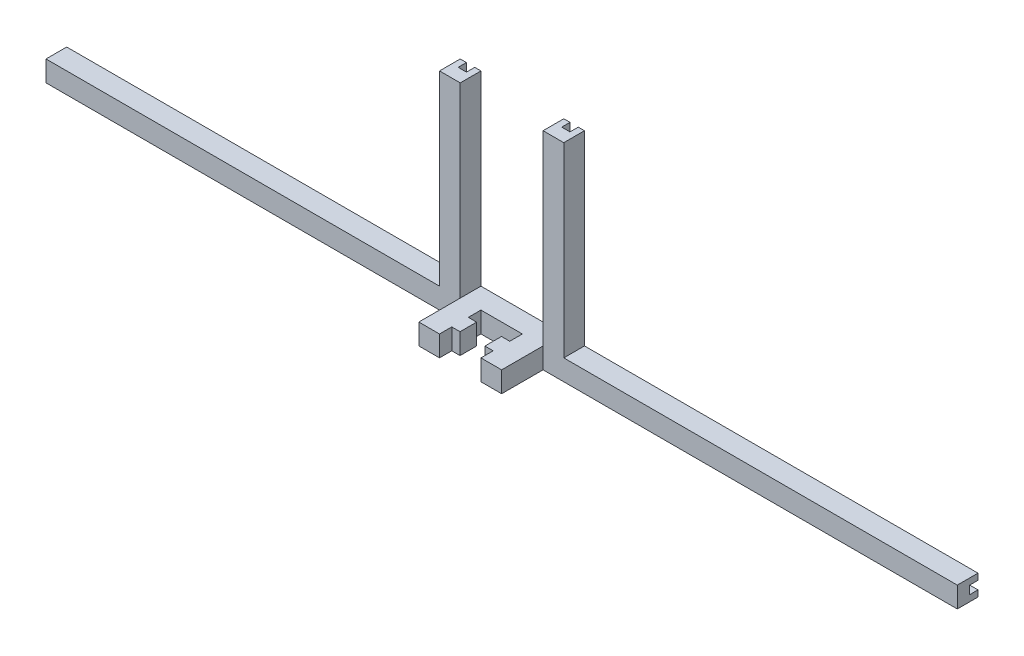
SolidWorks part; units mm, degrees
ref_plane "Front Plane" through (0, 0, 0) normal (0, 0, 1) x (1, 0, 0)
ref_plane "Top Plane" through (0, 0, 0) normal (0, 1, 0) x (1, 0, 0)
ref_plane "Right Plane" through (0, 0, 0) normal (1, 0, 0) x (0, 0, -1)
sketch "Sketch1" plane through (0, 0, 0) normal (0, 1, 0) x (1, 0, 0)
  line L0 (0, 151.5083) -> (0, 251.5083)
  line L17 (-31.6077, 251.5083) -> (68.3923, 251.5083)
  line L22 (-31.6077, 251.5083) -> (-31.6077, 151.5083)
  line L23 (-31.6077, 151.5083) -> (68.3923, 151.5083)
  line L24 (68.3923, 251.5083) -> (68.3923, 151.5083)
  line L25 (-31.6077, 181.0861) -> (-11.6077, 181.0861)
  line L26 (-31.6077, 181.0861) -> (-31.6077, 221.0861)
  line L27 (-31.6077, 221.0861) -> (-11.6077, 221.0861)
  line L28 (-11.6077, 181.0861) -> (-11.6077, 221.0861)
  line L29 (68.3923, 181.0861) -> (48.3923, 181.0861)
  line L30 (68.3923, 181.0861) -> (68.3923, 221.0861)
  line L31 (68.3923, 221.0861) -> (48.3923, 221.0861)
  line L32 (48.3923, 181.0861) -> (48.3923, 221.0861)
  line L34 (-81.6077, 301.5083) -> (118.3923, 301.5083)
  line L35 (-81.6077, 301.5083) -> (-81.6077, 151.5083)
  line L36 (-81.6077, 151.5083) -> (118.3923, 151.5083)
  line L37 (118.3923, 301.5083) -> (118.3923, 151.5083)
  dimension "D8" = 100
  dimension "D12" = 100
  dimension "D13" = 40
  dimension "D14" = 20
  dimension "D16" = 20
  dimension "D17" = 40
  dimension "D2" = 50
  dimension "D3" = 50
  dimension "D4" = 0
  dimension "D5" = 50
extrude "Boss-Extrude1" add sketch "Sketch1" along normal blind 50 contours L37 L34 L35 L36 L22 L17 L24 | L25 L28 L27 L22 | L32 L31 L30 L29
sketch "Sketch2" plane through (118.3923, 0, 0) normal (1, 0, 0) x (0, 0, -1)
  line L0 (301.5083, 50) -> (151.5083, 50) construction
  line L1 (251.5083, 50) -> (301.5083, 50)
  line L2 (251.5083, 50) -> (251.5083, 0)
  line L3 (251.5083, 0) -> (301.5083, 0)
  line L4 (301.5083, 50) -> (301.5083, 0)
  line L5 (301.5083, 0) -> (151.5083, 0) construction
  line L6 (301.5083, 50) -> (301.5083, 0) construction
  dimension "D3" = 50
  dimension "D1" = 50
  dimension "D2" = 0
extrude "Boss-Extrude2" add sketch "Sketch2" along normal blind 1000 contours L2 L1 L4 L3
sketch "Sketch3" plane through (-81.6077, 0, 0) normal (-1, 0, 0) x (0, 0, 1)
  line L0 (-301.5083, 0) -> (-151.5083, 0) construction
  line L1 (-301.5083, 50) -> (-251.5083, 50)
  line L2 (-301.5083, 50) -> (-301.5083, 0)
  line L3 (-301.5083, 0) -> (-251.5083, 0)
  line L4 (-251.5083, 50) -> (-251.5083, 0)
  dimension "D2" = 50
  dimension "D1" = 50
extrude "Boss-Extrude3" add sketch "Sketch3" along normal blind 1000
sketch "Sketch4" plane through (0, 50, 0) normal (0, 1, 0) x (1, 0, 0)
  line L0 (-1081.6077, 301.5083) -> (1118.3923, 301.5083) construction
  line L1 (-131.6077, 301.5083) -> (-81.6077, 301.5083)
  line L2 (-131.6077, 301.5083) -> (-131.6077, 251.5083)
  line L3 (-131.6077, 251.5083) -> (-81.6077, 251.5083)
  line L4 (-81.6077, 301.5083) -> (-81.6077, 251.5083)
  line L5 (1118.3923, 251.5083) -> (118.3923, 251.5083) construction
  line L6 (168.3923, 251.5083) -> (118.3923, 251.5083)
  line L7 (168.3923, 251.5083) -> (168.3923, 301.5083)
  line L8 (168.3923, 301.5083) -> (118.3923, 301.5083)
  line L9 (118.3923, 251.5083) -> (118.3923, 301.5083)
  line L10 (118.3923, 251.5083) -> (118.3923, 151.5083) construction
  dimension "D2" = 50
  dimension "D3" = 50
  dimension "D1" = 50
  dimension "D4" = 50
  dimension "D5" = 0
extrude "Boss-Extrude4" add sketch "Sketch4" along normal blind 450
sketch "Sketch6" plane through (0, 0, -301.5083) normal (0, 0, -1) x (-1, 0, 0)
  line L0 (-1118.3923, 50) -> (-1118.3923, 0) construction
  line L1 (-1118.3923, 35) -> (-468.3923, 35)
  line L2 (-1118.3923, 35) -> (-1118.3923, 15)
  line L3 (-1118.3923, 15) -> (-468.3923, 15)
  line L4 (-468.3923, 35) -> (-468.3923, 15)
  line L5 (-168.3923, 50) -> (-1118.3923, 50) construction
  line L6 (-18.3923, 50) -> (-18.3923, 0)
  line L7 (81.6077, 50) -> (-118.3923, 50) construction
  line L8 (1081.6077, 0) -> (-1118.3923, 0) construction
  line L9 (1081.6077, 15) -> (431.6077, 15)
  line L10 (431.6077, 35) -> (431.6077, 15)
  line L11 (1081.6077, 35) -> (431.6077, 35)
  line L12 (1081.6077, 35) -> (1081.6077, 15)
  line M2 (1081.6077, 0) -> (1081.6077, 50)
  dimension "D1" = 15
  dimension "D2" = 20
  dimension "D3" = 650
extrude "Cut-Extrude2" cut sketch "Sketch6" against normal blind 20 contours L11 L10 L9 M2 | L1 L4 L3 L2
sketch "Sketch7" plane through (0, 0, -301.5083) normal (0, 0, -1) x (-1, 0, 0)
  line L0 (-168.3923, 500) -> (-118.3923, 500) construction
  line L1 (-153.3923, 500) -> (-133.3923, 500)
  line L2 (-153.3923, 500) -> (-153.3923, 50)
  line L3 (-153.3923, 50) -> (-133.3923, 50)
  line L4 (-133.3923, 500) -> (-133.3923, 50)
  line L5 (-118.3923, 500) -> (-118.3923, 50) construction
  line L6 (-118.3923, 500) -> (81.6077, 500)
  line L7 (81.6077, 500) -> (-18.3923, 500)
  line L8 (-18.3923, 500) -> (-18.3923, 50)
  line L9 (81.6077, 50) -> (-118.3923, 50) construction
  line L10 (116.6077, 50) -> (96.6077, 50)
  line L11 (96.6077, 500) -> (96.6077, 50)
  line L12 (116.6077, 500) -> (96.6077, 500)
  line L13 (116.6077, 500) -> (116.6077, 50)
  line M17 (-118.3923, 500) -> (-168.3923, 500)
  dimension "D1" = 15
  dimension "D2" = 20
  dimension "D3" = 450
extrude "Cut-Extrude3" cut sketch "Sketch7" against normal blind 20 contours L4 L2 L3 M17 | L13 L10 L11 L12
equation "\"ScannerWidth\"= 800"
equation "\"ScannerLength\"= 400"
equation "\"SpineLength\"= 100"
equation "\"ScannerThickness\"= 50"
equation "\"ScannerHeight\" = 50"
equation "\"SpineWidth\"= 100"
equation "\"D8@Sketch1\"=\"SpineWidth\""
equation "\"TrainWidth\"= 40"
equation "\"TrainLength\"=20"
equation "\"D13@Sketch1\"= \"TrainWidth\""
equation "\"D14@Sketch1\"=\"TrainLength\""
equation "\"D16@Sketch1\"=\"TrainLength\""
equation "\"D17@Sketch1\"=\"TrainWidth\""
equation "\"Armwidth\"= 50"
equation "\"Armlength\"=1000"
equation "\"RailWidth\"= 20"
equation "\"RailLength\"= 650"
equation "\"RailDepth\"=20"
equation "\"HeadTowerHeight\"= 450"
equation "\"HeadSeparation\"= 200"
equation "\"HeadTowerRingRailWidth\"= 20"
equation "\"HeadTowerRingRailDepth\"= 20"
equation "\"D12@Sketch1\"=\"SpineLength\""
equation "\"D2@Sketch1\"=\"ScannerThickness\""
equation "\"D3@Sketch1\"=\"ScannerThickness\""
equation "\"D5@Sketch1\"=\"ScannerThickness\""
equation "\"D1@Boss-Extrude1\"=\"ScannerHeight\""
equation "\"D1@Sketch2\"=\"Armwidth\""
equation "\"D2@Sketch2\"=0"
equation "\"D1@Boss-Extrude2\"=\"Armlength\""
equation "\"D1@Sketch3\"=\"Armwidth\""
equation "\"D1@Boss-Extrude3\"=\"Armlength\""
equation "\"D1@Sketch4\"=\"ScannerThickness\""
equation "\"D4@Sketch4\"=\"ScannerThickness\""
equation "\"D1@Boss-Extrude4\"=\"HeadTowerHeight\""
equation "\"D1@Sketch6\"=(\"ScannerThickness\"-\"RailWidth\")/2"
equation "\"D2@Sketch6\"=\"RailWidth\""
equation "\"D3@Sketch6\"=\"RailLength\""
equation "\"D1@Cut-Extrude2\"=\"RailDepth\""
equation "\"D1@Sketch7\"=(\"ScannerThickness\"-\"HeadTowerRingRailWidth\")/2"
equation "\"D2@Sketch7\"=\"HeadTowerRingRailWidth\""
equation "\"D3@Sketch7\"=\"HeadTowerHeight\""
equation "\"D1@Cut-Extrude3\"=\"HeadTowerRingRailDepth\""
equation "\"HeadLength\"= 30"
equation "\"HeadScannerHeight\"=5"
